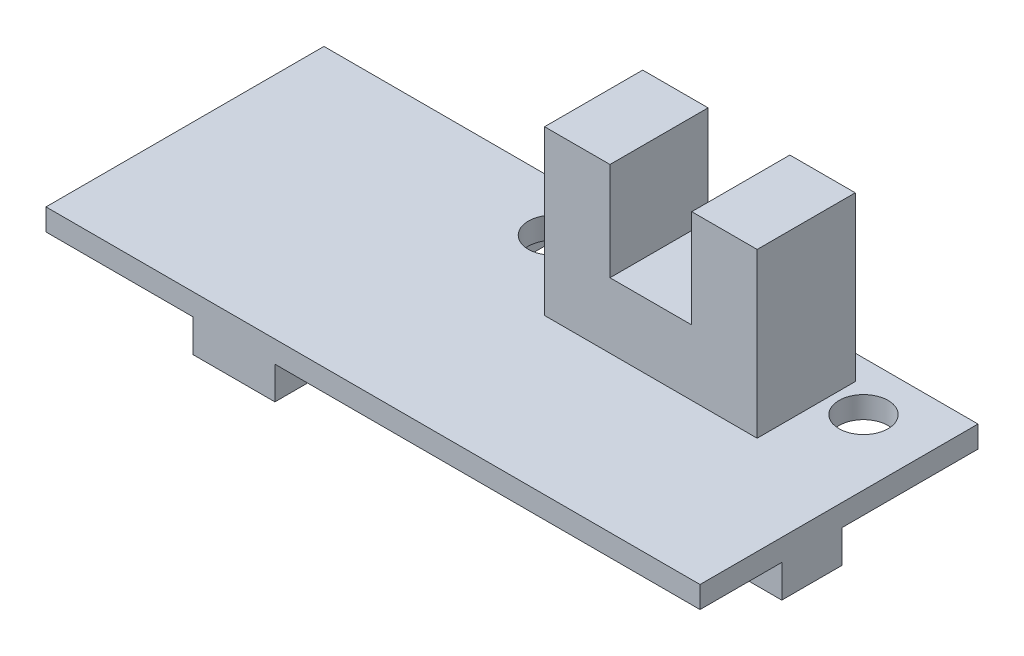
SolidWorks part; units mm, degrees
ref_plane "Спереди" through (0, 0, 0) normal (0, 0, 1) x (1, 0, 0)
ref_plane "Сверху" through (0, 0, 0) normal (0, 1, 0) x (1, 0, 0)
ref_plane "Справа" through (0, 0, 0) normal (1, 0, 0) x (0, 0, -1)
sketch "Эскиз1" plane through (0, 0, 0) normal (0, 1, 0) x (1, 0, 0)
  line L1 (-20, 8.5) -> (20, 8.5)
  line L2 (-20, 8.5) -> (-20, -8.5)
  line L3 (-20, -8.5) -> (20, -8.5)
  line L4 (20, 8.5) -> (20, -8.5)
  line L5 (-20, 8.5) -> (20, -8.5) construction
  line L6 (-20, -8.5) -> (20, 8.5) construction
  point P0 (0, 0)
  dimension "D1" = 17
  dimension "D2" = 40
extrude "Бобышка-Вытянуть1" add sketch "Эскиз1" along normal blind 1.33
sketch "Эскиз2" plane through (0, 1.33, 0) normal (0, 1, 0) x (1, 0, 0)
  line L1 (14, 6.993) -> (10, 6.993)
  line L2 (14, 6.993) -> (14, 0.993)
  line L3 (14, 0.993) -> (10, 0.993)
  line L4 (10, 6.993) -> (10, 0.993)
  line L5 (20, -8.5) -> (20, 8.5) construction
  line L6 (5, 6.993) -> (1, 6.993)
  line L7 (5, 6.993) -> (5, 0.993)
  line L8 (5, 0.993) -> (1, 0.993)
  line L9 (1, 6.993) -> (1, 0.993)
  dimension "D1" = 4
  dimension "D2" = 6
  dimension "D3" = 5
  dimension "D4" = 6
sketch "Эскиз3" plane through (0, 0, 0) normal (0, -1, 0) x (1, 0, 0)
  line L0 (20, -8.5) -> (-20, -8.5) construction
  line L1 (-6, -8.5) -> (-11, -8.5)
  line L2 (-6, -8.5) -> (-6, 8.5)
  line L3 (-6, 8.5) -> (-11, 8.5)
  line L4 (-11, -8.5) -> (-11, 8.5)
  line L5 (-20, 8.5) -> (20, 8.5) construction
  line L6 (20, 8.5) -> (20, -8.5) construction
  line L7 (20, -0.19) -> (-6, -0.19)
  line L8 (20, -0.19) -> (20, 3.5)
  line L9 (20, 3.5) -> (-6, 3.5)
  line L10 (-6, -0.19) -> (-6, 3.5)
  line M2 (20, 8.5) -> (-20, 8.5)
  line M4 (-20, -8.5) -> (20, -8.5)
  dimension "D1" = 5
  dimension "D2" = 3.69
  dimension "D3" = 26
  dimension "D4" = 5
extrude "Бобышка-Вытянуть3" add sketch "Эскиз3" along normal blind 2 contours L4 L2 M4 M2 | L7 L10 L9 L8
sketch "Эскиз4" plane through (0, 0, 0) normal (0, -1, 0) x (1, 0, 0)
  line L0 (20, -0.19) -> (20, -8.5) construction
  line L1 (20, -8.5) -> (-6, -8.5) construction
  circle A0 centre (16, -5.5) radius 1.5
  circle A1 centre (-3, -5.5) radius 1.5
  dimension "D1" = 3
  dimension "D2" = 4
  dimension "D3" = 23
  dimension "D4" = 3
  dimension "D5" = 3
extrude "Вырез-Вытянуть1" cut sketch "Эскиз4" against normal through all
extrude "Бобышка-Вытянуть4" add sketch "Эскиз2" along normal blind 10
sketch "Эскиз5" plane through (0, 1.33, 0) normal (0, 1, 0) x (1, 0, 0)
  line L1 (10, 6.993) -> (5, 6.993)
  line L2 (10, 6.993) -> (10, 0.993)
  line L3 (10, 0.993) -> (5, 0.993)
  line L4 (5, 6.993) -> (5, 0.993)
  point P6 (0, 0)
  dimension "D1" = 5
extrude "Бобышка-Вытянуть5" add sketch "Эскиз5" along normal blind 4
